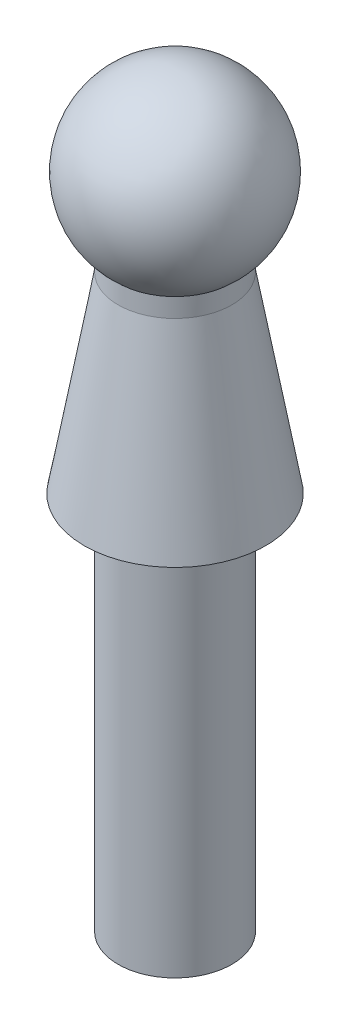
SolidWorks part; units mm, degrees
ref_plane "Front Plane" through (0, 0, 0) normal (0, 0, 1) x (1, 0, 0)
ref_plane "Top Plane" through (0, 0, 0) normal (0, 1, 0) x (1, 0, 0)
ref_plane "Right Plane" through (0, 0, 0) normal (1, 0, 0) x (0, 0, -1)
sketch "Sketch1" plane through (0, 0, 0) normal (0, 0, 1) x (1, 0, 0)
  line L0 (0, 0) -> (6, 0)
  line L1 (6, 0) -> (6, 40)
  line L2 (6, 40) -> (9.5633, 40)
  line L3 (9.5633, 40) -> (6, 60.2083)
  line L4 (6, 60.2083) -> (6, 62.2083)
  line L5 (0, 0) -> (0, 152.6876) construction
  line L6 (0, 0) -> (0, 78.7523)
  arc A0 (6, 62.2083) -> (0, 78.7523) centre (0, 69.3923) ccw
  dimension "D4" = 9.36
  dimension "D1" = 10
  dimension "D3" = 6
  dimension "D5" = 2
  dimension "D2" = 69.3923
  dimension "D6" = 40
revolve "Revolve1" add sketch "Sketch1" angle 360 about L5
cosmetic thread "Cosmetic Thread1"
sketch "Sketch5" plane through (0, 40, 0) normal (0, -1, 0) x (1, 0, 0)
  circle A0 centre (0, 0) radius 9.5633 construction
  point P0 (-9.5633, 0)
equation "\"D4@Sketch1\"=(\"THREADRADIUS\"*1.3*1.2)"
equation "\"THREADRADIUS\"= 6mm"
equation "\"D3@Sketch1\"=\"THREADRADIUS\""
